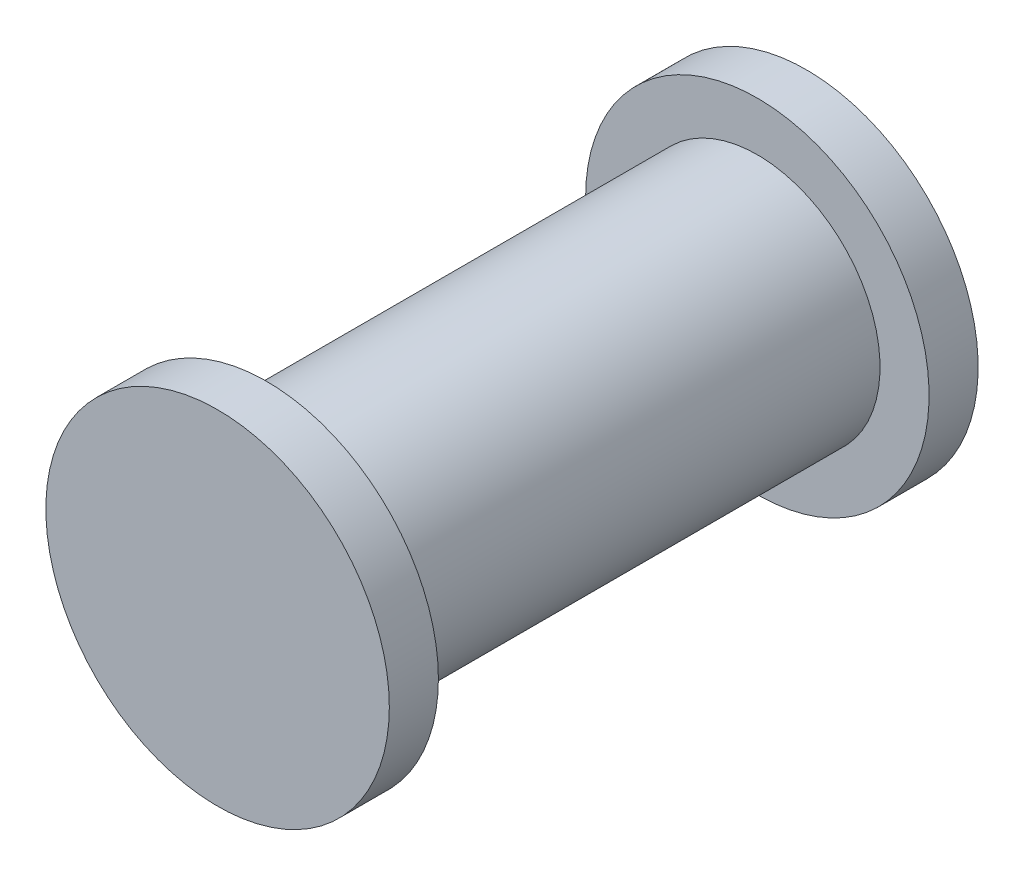
SolidWorks part; units mm, degrees
ref_plane "Front Plane" through (0, 0, 0) normal (0, 0, 1) x (1, 0, 0)
ref_plane "Top Plane" through (0, 0, 0) normal (0, 1, 0) x (1, 0, 0)
ref_plane "Right Plane" through (0, 0, 0) normal (1, 0, 0) x (0, 0, -1)
sketch "Sketch1" plane through (0, 0, 0) normal (0, 0, 1) x (1, 0, 0)
  circle A0 centre (0, 0) radius 12.5
  dimension "D1" = 25
extrude "Boss-Extrude1" add sketch "Sketch1" along normal blind 50
sketch "Sketch2" plane through (0, 0, 50) normal (0, 0, 1) x (1, 0, 0)
  circle A0 centre (0, 0) radius 17.5
  dimension "D1" = 35
extrude "Boss-Extrude2" add sketch "Sketch2" along normal blind 5
sketch "Sketch3" plane through (0, 0, 0) normal (0, 0, -1) x (-1, 0, 0)
  circle A0 centre (0, 0) radius 17.5
  dimension "D1" = 35
extrude "Boss-Extrude3" add sketch "Sketch3" along normal blind 5
